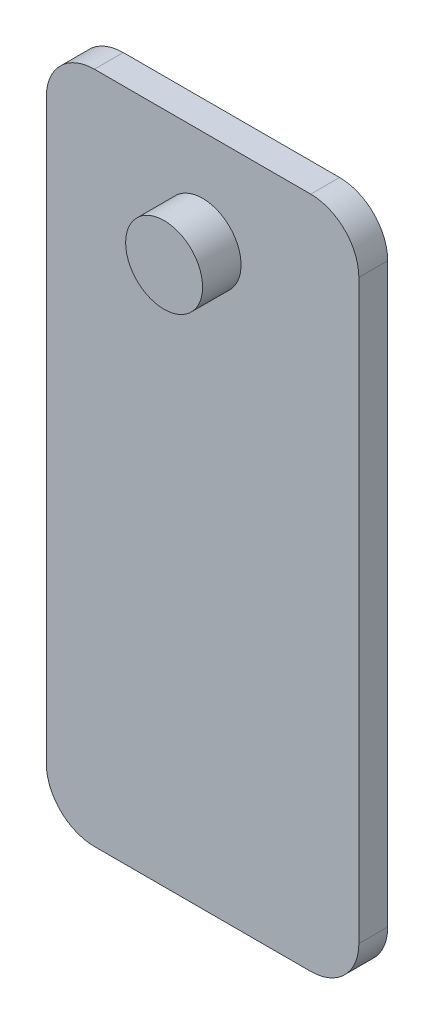
SolidWorks part; units mm, degrees
ref_plane "Front Plane" through (0, 0, 0) normal (0, 0, 1) x (1, 0, 0)
ref_plane "Top Plane" through (0, 0, 0) normal (0, 1, 0) x (1, 0, 0)
ref_plane "Right Plane" through (0, 0, 0) normal (1, 0, 0) x (0, 0, -1)
sketch "Sketch1" plane through (0, 0, 0) normal (0, 0, 1) x (1, 0, 0)
  line L1 (16.25, 35) -> (-16.25, 35)
  line L2 (16.25, 35) -> (16.25, -35)
  line L3 (16.25, -35) -> (-16.25, -35)
  line L4 (-16.25, 35) -> (-16.25, -35)
  line L5 (16.25, 35) -> (-16.25, -35) construction
  line L6 (16.25, -35) -> (-16.25, 35) construction
  point P0 (0, 0)
  dimension "D1" = 32.5
  dimension "D2" = 70
extrude "Boss-Extrude1" add sketch "Sketch1" along normal blind 3
sketch "Midlines" plane through (0, 0, 3) normal (0, 0, 1) x (1, 0, 0)
  line L0 (0, 35) -> (0, -35) construction
  line L1 (-16.25, -35) -> (16.25, -35) construction
  line L2 (16.25, 0) -> (-16.25, 0) construction
  line L3 (-16.25, 35) -> (-16.25, -35) construction
  point P6 (0, 0)
  point P12 (0, 0)
fillet "Fillet1" radius 5 4 edges at (-16.25, -35, 1.5) (16.25, -35, 1.5) (16.25, 35, 1.5) (-16.25, 35, 1.5)
sketch "Sketch2" plane through (0, 0, 3) normal (0, 0, 1) x (1, 0, 0)
  line L0 (11.25, 35) -> (-11.25, 35) construction
  line L1 (16.25, -30) -> (16.25, 30) construction
  circle A0 centre (0, 25) radius 4
  dimension "D1" = 10
  dimension "D2" = 16.25
extrude "Boss-Extrude2" add sketch "Sketch2" along normal blind 4
scale "Scale1" scale about centroid uniform scaling yes scale factor 1.5
